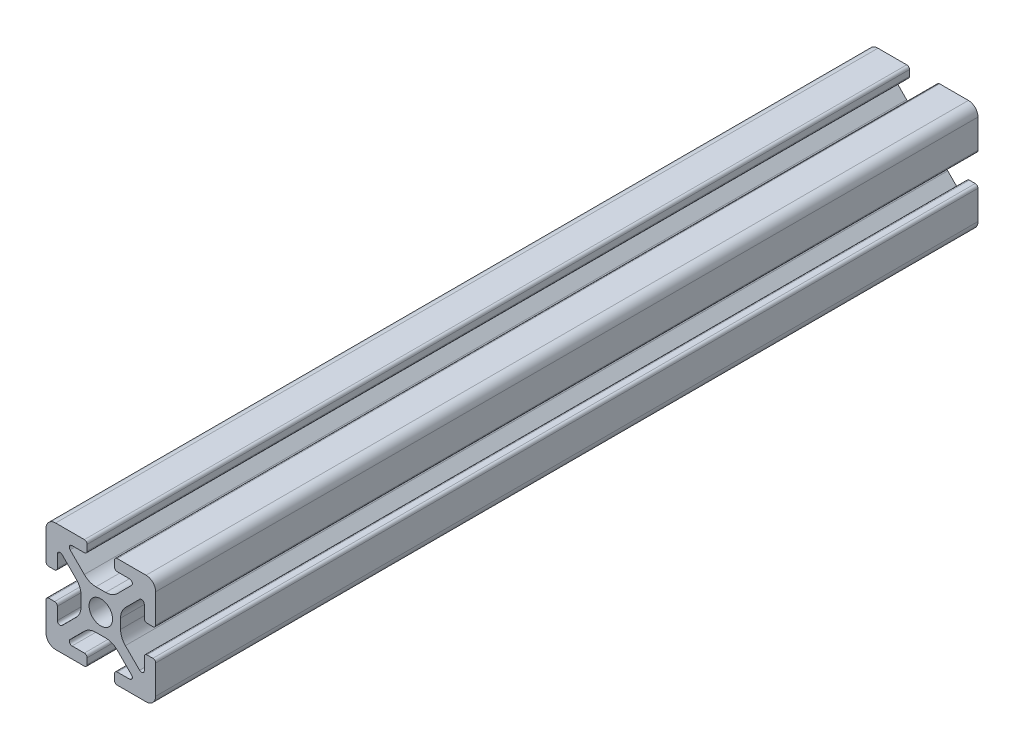
SolidWorks part; units mm, degrees
material "1060 Alloy"
ref_plane "Front Plane" through (0, 0, 0) normal (0, 0, 1) x (1, 0, 0)
ref_plane "Top Plane" through (0, 0, 0) normal (0, 1, 0) x (1, 0, 0)
ref_plane "Right Plane" through (0, 0, 0) normal (1, 0, 0) x (0, 0, -1)
sketch "Sketch2" plane through (0, 0, 0) normal (0, 0, 1) x (1, 0, 0)
  line L0 (0, 10) -> (0, -10) construction
  line L1 (-10, 0) -> (10, 0) construction
  line L2 (2.5, -10) -> (10, -10)
  line L3 (10, -10) -> (10, -2.5)
  line L4 (2.5, -10) -> (2.5, -7.9246)
  line L5 (2.5, -7.9246) -> (6.4571, -7.9246)
  line L6 (6.4571, -7.9246) -> (2.1325, -3.6)
  line L7 (0, 0) -> (10, -10) construction
  line L8 (10, -2.5) -> (7.9246, -2.5)
  line L9 (7.9246, -2.5) -> (7.9246, -6.4571)
  line L10 (7.9246, -6.4571) -> (3.6, -2.1325)
  line L11 (5.7623, -4.2948) -> (4.2948, -5.7623) construction
  circle A0 centre (0, 0) radius 2.15
  arc A1 (5.25, -7.9246) -> (5.6036, -7.0711) centre (5.25, -7.4246) ccw construction
  point P8 (0, -3.6)
  point P16 (5.0286, -5.0286)
  dimension "Center Hole Diameter" = 4.3
  dimension "D3" = 0.5
  dimension "Rail Height" = 20
  dimension "Rail Width" = 20
  dimension "T-Slot Width" = 5
  dimension "Slot Depth" = 6.4
  dimension "Slot Inner Width" = 11.5
sketch "Sketch3" plane through (0, 0, 0) normal (1, 0, 0) x (0, 0, -1)
  line L0 (-76.2, -10) -> (76.2, -10) construction
  line L1 (-50.8, 0) -> (50.8, 0) construction
  line L2 (0, 10) -> (0, -10) construction
  line L3 (0, 10) -> (0, -10) construction
  point P6 (-50.8, 0)
  point P8 (50.8, 0)
  dimension "Length" = 152.4
  dimension "D1" = 25.4
sketch "Sketch4" plane through (0, 0, 0) normal (0, 0, 1) x (1, 0, 0)
  line L0 (3, -10) -> (8.25, -10)
  line L1 (2.5, -10) -> (10, -10) construction
  line L2 (2.5, -10) -> (2.5, -7.9246) construction
  line L3 (2.5, -7.9246) -> (6.4571, -7.9246) construction
  line L4 (2.5, -8.4246) -> (2.5, -9.5)
  line L5 (3, -7.9246) -> (5.25, -7.9246)
  line L6 (0, -3.6) -> (0.8898, -3.6)
  line L7 (6.4571, -7.9246) -> (2.1325, -3.6) construction
  line L8 (3.0112, -4.4787) -> (5.6036, -7.0711)
  line L9 (10, -10) -> (10, -2.5) construction
  line L10 (7.9246, -6.4571) -> (3.6, -2.1325) construction
  line L11 (7.9246, -2.5) -> (7.9246, -6.4571) construction
  line L12 (7.9246, -5.25) -> (7.9246, -3)
  line L13 (10, -2.5) -> (7.9246, -2.5) construction
  line L14 (8.4246, -2.5) -> (9.5, -2.5)
  line L15 (10, -3) -> (10, -8.25)
  line L16 (7.0711, -5.6036) -> (4.4787, -3.0112)
  line L17 (3.6, 0) -> (3.6, -0.8898)
  line L18 (-10, 0) -> (10, 0) construction
  line L19 (0, -3.6) -> (0, -2.15)
  line L20 (0, 10) -> (0, -10) construction
  line L21 (3.6, 0) -> (2.15, 0)
  arc A0 (2.5, -9.5) -> (3, -10) centre (3, -9.5) ccw
  arc A1 (5.25, -7.9246) -> (5.6036, -7.0711) centre (5.25, -7.4246) ccw construction
  arc A2 (2.5, -8.4246) -> (3, -7.9246) centre (3, -8.4246) cw
  arc A3 (5.25, -7.9246) -> (5.6036, -7.0711) centre (5.25, -7.4246) ccw
  arc A4 (0.8898, -3.6) -> (3.0112, -4.4787) centre (0.8898, -6.6) cw
  arc A5 (8.25, -10) -> (10, -8.25) centre (8.25, -8.25) ccw
  arc A6 (7.0711, -5.6036) -> (7.9246, -5.25) centre (7.4246, -5.25) ccw
  arc A7 (7.9246, -3) -> (8.4246, -2.5) centre (8.4246, -3) cw
  arc A8 (9.5, -2.5) -> (10, -3) centre (9.5, -3) cw
  arc A9 (4.4787, -3.0112) -> (3.6, -0.8898) centre (6.6, -0.8898) cw
  circle A10 centre (0, 0) radius 2.15 construction
  arc A11 (0, -2.15) -> (2.15, 0) centre (0, 0) ccw
  dimension "D1" = 1.75
  dimension "D2" = 3
extrude "Boss-Extrude1" add sketch "Sketch4" along normal mid plane 152.4
mirror "Mirror1" about plane through (0, 0, 0) normal (1, 0, 0) of bodies 134
mirror "Mirror2" about plane through (0, 0, 0) normal (0, 1, 0) of bodies 135
sketch "Sketch5" plane through (0, 0, 76.2) normal (0, 0, 1) x (1, 0, 0)
  line L1 (-13.9539, 12.3566) -> (13.8334, 12.3566)
  line L2 (-13.9539, 12.3566) -> (-13.9539, -13.6827)
  line L3 (-13.9539, -13.6827) -> (13.8334, -13.6827)
  line L4 (13.8334, 12.3566) -> (13.8334, -13.6827)
extrude "Cut-Extrude1" cut sketch "Sketch5" against normal blind 2.4
equation "\"D3@Sketch2\"=\"T-Slot Width@Sketch2\"*0.1"
equation "\"D1@Sketch4\"=\"D3@Sketch2\"*3.5"
equation "\"D2@Sketch4\"=\"D3@Sketch2\"*6"
equation "\"D1@Boss-Extrude1\"=\"Length@Sketch3\""
